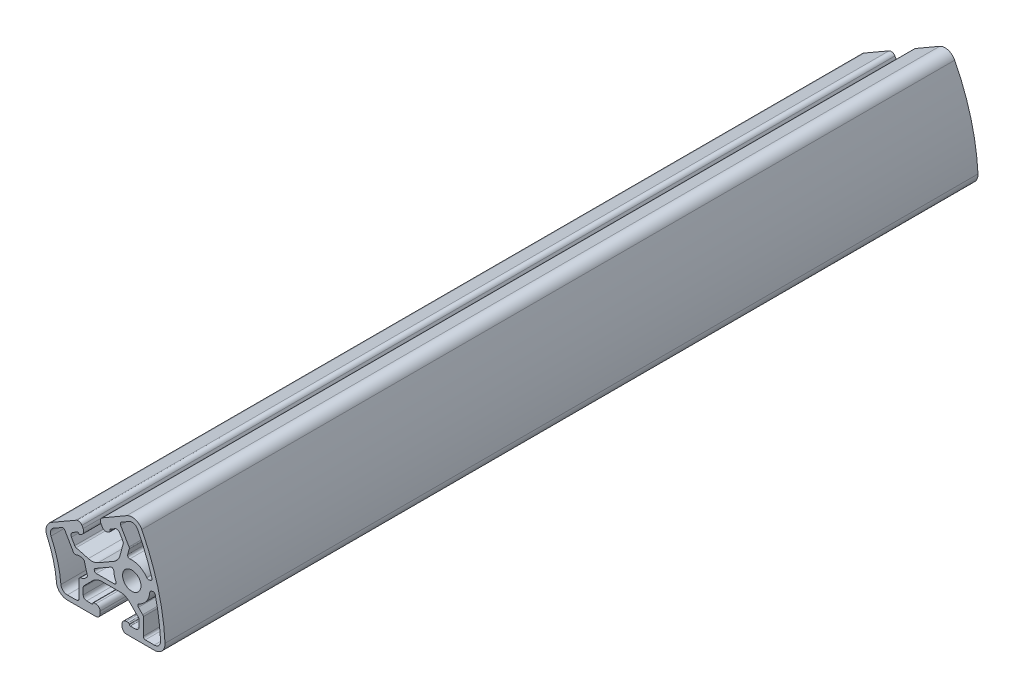
SolidWorks part; units mm, degrees
material "6105-T5 Aluminum"
ref_plane "Front Plane" through (0, 0, 0) normal (0, 0, 1) x (1, 0, 0)
ref_plane "Top Plane" through (0, 0, 0) normal (0, 1, 0) x (1, 0, 0)
ref_plane "Right Plane" through (0, 0, 0) normal (1, 0, 0) x (0, 0, -1)
sketch "Sketch1" plane through (0, 0, 0) normal (0, 0, 1) x (1, 0, 0)
  line L0 (-17.472, -2.5855) -> (-16.4239, -6.4969)
  line L1 (-19.4985, -9.2957) -> (-19.4985, -15.6628)
  line L2 (-20.2504, -16.4228) -> (-23.7785, -16.4605)
  line L3 (-28.8231, 2.3659) -> (-25.7487, 4.0973)
  line L4 (-24.7176, 3.8151) -> (-21.5341, -1.6989)
  line L5 (7.1909, 0.2421) -> (7.7229, 0.3846)
  line L6 (8.2601, -16.4578) -> (5.0023, -16.4228)
  line L7 (4.2504, -15.6628) -> (4.2504, -9.3952)
  line L8 (4.0278, -8.8578) -> (2.4722, -7.3021)
  line L9 (-1.5101, 7.5599) -> (-0.9407, 9.685)
  line L10 (-1.0166, 10.2617) -> (-4.1504, 15.6896)
  line L11 (-3.8793, 16.7237) -> (-1.0754, 18.3829)
  line L12 (6.8805, 3.5283) -> (6.3485, 3.3858)
  line L13 (-6.5195, -4.2692) -> (-13.0965, -4.2692)
  line L14 (-13.4765, -2.851) -> (-7.7807, 0.4375)
  line L15 (-2.0596, -18.1044) -> (8.2792, -18.1044)
  line L16 (-1.8822, 19.8185) -> (-10.8359, 14.6491)
  line L17 (-11.3528, 12.5222) -> (-10.8956, 11.7304)
  line L18 (-8.8041, 11.13) -> (-8.1373, 11.515)
  line L19 (-7.9918, 12.0224) -> (-8.0052, 12.0476)
  line L20 (-7.8597, 12.555) -> (-6.2048, 13.5105)
  line L21 (-4.4702, 13.0457) -> (-3.2502, 10.9325)
  line L22 (-3.1614, 10.258) -> (-4.3643, 5.7687)
  line L23 (-6.577, 2.8849) -> (-12.4327, -0.4958)
  line L24 (-16.0365, -0.9703) -> (-20.5258, 0.2326)
  line L25 (-21.0655, 0.6468) -> (-22.2856, 2.76)
  line L26 (-21.8208, 4.4946) -> (-20.1659, 5.45)
  line L27 (-19.6537, 5.3223) -> (-19.6386, 5.2981)
  line L28 (-19.1264, 5.1704) -> (-18.5146, 5.5237)
  line L29 (-17.9383, 7.6746) -> (-18.3954, 8.4664)
  line L30 (-20.5464, 9.0427) -> (-29.662, 3.7798)
  line L31 (-23.7982, -18.1044) -> (-13.2723, -18.1044)
  line L32 (-11.6977, -16.5298) -> (-11.6977, -15.6155)
  line L33 (-13.2723, -14.0409) -> (-13.9788, -14.0409)
  line L34 (-14.3585, -14.4076) -> (-14.3595, -14.4361)
  line L35 (-14.7392, -14.8028) -> (-16.6501, -14.8028)
  line L36 (-17.9199, -13.533) -> (-17.9199, -11.0929)
  line L37 (-17.6596, -10.4644) -> (-14.3732, -7.178)
  line L38 (-11.015, -5.787) -> (-4.2534, -5.787)
  line L39 (-0.8952, -7.178) -> (2.3912, -10.4644)
  line L40 (2.6515, -11.0929) -> (2.6515, -13.533)
  line L41 (1.3817, -14.8028) -> (-0.5292, -14.8028)
  line L42 (-0.9089, -14.4361) -> (-0.9099, -14.4076)
  line L43 (-1.2896, -14.0409) -> (-2.0596, -14.0409)
  line L44 (-3.5707, -15.6066) -> (-3.5707, -16.5209)
  arc A0 (-16.5361, -7.1304) -> (-16.4239, -6.4969) centre (-17.158, -6.6936) ccw
  arc A1 (-18.8445, -8.5432) -> (-16.5361, -7.1304) centre (-19.3185, -5.1764) ccw
  arc A2 (-18.8445, -8.5432) -> (-19.4985, -9.2957) centre (-18.7385, -9.2957) ccw
  arc A3 (-20.2504, -16.4228) -> (-19.4985, -15.6628) centre (-20.2585, -15.6628) ccw
  arc A4 (-26.1439, -14.3246) -> (-23.7785, -16.4605) centre (-23.8037, -14.1106) ccw
  arc A5 (-26.1439, -14.3246) -> (-29.8036, -0.6665) centre (-67.6148, -18.1173) ccw
  arc A6 (-28.8231, 2.3659) -> (-29.8036, -0.6665) centre (-27.6699, 0.3183) ccw
  arc A7 (-24.7176, 3.8151) -> (-25.7487, 4.0973) centre (-25.3758, 3.4351) ccw
  arc A8 (-21.5341, -1.6989) -> (-20.5914, -2.0236) centre (-20.8759, -1.3189) ccw
  arc A9 (-17.8859, -2.093) -> (-20.5914, -2.0236) centre (-19.3185, -5.1764) ccw
  arc A10 (-17.472, -2.5855) -> (-17.8859, -2.093) centre (-18.2061, -2.7822) ccw
  arc A11 (2.7006, -6.0703) -> (2.4722, -7.3021) centre (3.0096, -6.7647) ccw
  arc A12 (2.7006, -6.0703) -> (6.6293, -0.4415) centre (0, 0) ccw
  arc A13 (7.1909, 0.2421) -> (6.6293, -0.4415) centre (7.3876, -0.492) ccw
  arc A14 (8.6594, -0.1754) -> (7.7229, 0.3846) centre (7.9196, -0.3495) ccw
  arc A15 (10.6321, -13.984) -> (8.6594, -0.1754) centre (-67.6148, -18.1173) ccw
  arc A16 (8.2601, -16.4578) -> (10.6321, -13.984) centre (8.2854, -14.1079) ccw
  arc A17 (4.2504, -15.6628) -> (5.0023, -16.4228) centre (5.0104, -15.6628) ccw
  arc A18 (4.2504, -9.3952) -> (4.0278, -8.8578) centre (3.4904, -9.3952) ccw
  arc A19 (-1.5101, 7.5599) -> (-0.6963, 6.6074) centre (-0.776, 7.3632) ccw
  arc A20 (-0.9407, 9.685) -> (-1.0166, 10.2617) centre (-1.6748, 9.8817) ccw
  arc A21 (-3.8793, 16.7237) -> (-4.1504, 15.6896) centre (-3.4922, 16.0696) ccw
  arc A22 (2.2157, 17.4265) -> (-1.0754, 18.3829) centre (0.1214, 16.3605) ccw
  arc A23 (7.4116, 4.4816) -> (2.2157, 17.4265) centre (-67.6148, -18.1173) ccw
  arc A24 (6.8805, 3.5283) -> (7.4116, 4.4816) centre (6.6838, 4.2624) ccw
  arc A25 (5.5204, 3.697) -> (6.3485, 3.3858) centre (6.1518, 4.1199) ccw
  arc A26 (5.5204, 3.697) -> (-0.6963, 6.6074) centre (0, 0) ccw
  arc A27 (-6.641, -0.198) -> (-7.7807, 0.4375) centre (-7.4007, -0.2207) ccw
  arc A28 (-6.641, -0.198) -> (-5.8503, -3.149) centre (0, 0) ccw
  arc A29 (-6.5195, -4.2692) -> (-5.8503, -3.149) centre (-6.5195, -3.5092) ccw
  arc A30 (-13.4765, -2.851) -> (-13.0965, -4.2692) centre (-13.0965, -3.5092) ccw
  circle A31 centre (0, 0) radius 3.4
  arc A32 (8.2792, -18.1044) -> (12.2736, -13.8932) centre (8.2792, -14.1044) ccw
  arc A33 (12.2736, -13.8932) -> (3.6826, 18.1687) centre (-67.6148, -18.1173) ccw
  arc A34 (3.6826, 18.1687) -> (-1.8822, 19.8185) centre (0.1178, 16.3544) ccw
  arc A35 (-10.8359, 14.6491) -> (-11.3528, 12.5222) centre (-9.969, 13.3121) ccw
  arc A36 (-10.8956, 11.7304) -> (-8.8041, 11.13) centre (-9.5411, 12.5058) ccw
  arc A37 (-8.1373, 11.515) -> (-7.9918, 12.0224) centre (-8.3273, 11.844) ccw
  arc A38 (-7.8597, 12.555) -> (-8.0052, 12.0476) centre (-7.6697, 12.226) ccw
  arc A39 (-4.4702, 13.0457) -> (-6.2048, 13.5105) centre (-5.5699, 12.4107) ccw
  arc A40 (-3.1614, 10.258) -> (-3.2502, 10.9325) centre (-4.02, 10.488) ccw
  arc A41 (-6.577, 2.8849) -> (-4.3643, 5.7687) centre (-8.9516, 6.9979) ccw
  arc A42 (-16.0365, -0.9703) -> (-12.4327, -0.4958) centre (-14.8073, 3.6171) ccw
  arc A43 (-21.0655, 0.6468) -> (-20.5258, 0.2326) centre (-20.2957, 1.0912) ccw
  arc A44 (-21.8208, 4.4946) -> (-22.2856, 2.76) centre (-21.1859, 3.3949) ccw
  arc A45 (-19.6537, 5.3223) -> (-20.1659, 5.45) centre (-19.976, 5.121) ccw
  arc A46 (-19.6386, 5.2981) -> (-19.1264, 5.1704) centre (-19.3164, 5.4995) ccw
  arc A47 (-18.5146, 5.5237) -> (-17.9383, 7.6746) centre (-19.3019, 6.8873) ccw
  arc A48 (-18.3954, 8.4664) -> (-20.5464, 9.0427) centre (-19.759, 7.6791) ccw
  arc A49 (-29.662, 3.7798) -> (-31.2941, -1.36) centre (-27.662, 0.3157) ccw
  arc A50 (-27.7815, -14.4692) -> (-31.2941, -1.36) centre (-67.6148, -18.1173) ccw
  arc A51 (-27.7815, -14.4692) -> (-23.7982, -18.1044) centre (-23.7982, -14.1044) ccw
  arc A52 (-13.2723, -18.1044) -> (-11.6977, -16.5298) centre (-13.2723, -16.5298) ccw
  arc A53 (-11.6977, -15.6155) -> (-13.2723, -14.0409) centre (-13.2723, -15.6155) ccw
  arc A54 (-13.9788, -14.0409) -> (-14.3585, -14.4076) centre (-13.9788, -14.4209) ccw
  arc A55 (-14.7392, -14.8028) -> (-14.3595, -14.4361) centre (-14.7392, -14.4229) ccw
  arc A56 (-17.9199, -13.533) -> (-16.6501, -14.8028) centre (-16.6501, -13.533) ccw
  arc A57 (-17.6596, -10.4644) -> (-17.9199, -11.0929) centre (-17.031, -11.0929) ccw
  arc A58 (-11.015, -5.787) -> (-14.3732, -7.178) centre (-11.015, -10.5362) ccw
  arc A59 (-0.8952, -7.178) -> (-4.2534, -5.787) centre (-4.2534, -10.5362) ccw
  arc A60 (2.6515, -11.0929) -> (2.3912, -10.4644) centre (1.7626, -11.0929) ccw
  arc A61 (1.3817, -14.8028) -> (2.6515, -13.533) centre (1.3817, -13.533) ccw
  arc A62 (-0.9089, -14.4361) -> (-0.5292, -14.8028) centre (-0.5292, -14.4229) ccw
  arc A63 (-0.9099, -14.4076) -> (-1.2896, -14.0409) centre (-1.2896, -14.4209) ccw
  arc A64 (-2.0596, -14.0409) -> (-3.5707, -15.6066) centre (-2.01, -15.6009) ccw
  arc A65 (-3.5707, -16.5209) -> (-2.0596, -18.1044) centre (-1.9773, -16.5131) ccw
extrude "Extrude1" add sketch "Sketch1" against normal blind 300
